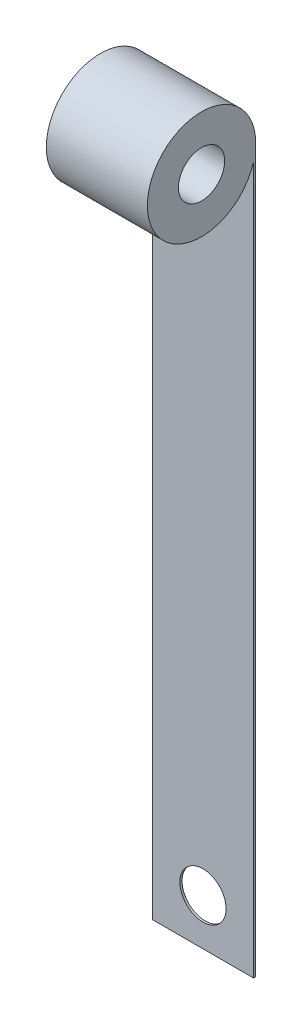
SolidWorks part; units mm, degrees
ref_plane "前视基准面" through (0, 0, 0) normal (0, 0, 1) x (1, 0, 0)
ref_plane "上视基准面" through (0, 0, 0) normal (0, 1, 0) x (1, 0, 0)
ref_plane "右视基准面" through (0, 0, 0) normal (1, 0, 0) x (0, 0, -1)
sketch "草图1" plane through (0, 0, 0) normal (1, 0, 0) x (0, 0, -1)
  circle A0 centre (0, 0) radius 3.75
  circle A1 centre (0, 0) radius 1.6
  dimension "D1" = 7.5
  dimension "D2" = 3.2
extrude "凸台-拉伸1" add sketch "草图1" along normal blind 7
sketch "草图2" plane through (0, 0, 0) normal (0, 1, 0) x (1, 0, 0)
  line L0 (7, -3.75) -> (7, 3.75) construction
  line L1 (0, 3.75) -> (7, 3.75)
  line L2 (0, 3.75) -> (0, 3.6)
  line L3 (0, 3.6) -> (7, 3.6)
  line L4 (7, 3.75) -> (7, 3.6)
  line L5 (0, 3.75) -> (7, 3.6) construction
  line L6 (0, 3.6) -> (7, 3.75) construction
  point P4 (3.5, 3.675)
  dimension "D1" = 0.15
extrude "凸台-拉伸2" add sketch "草图2" against normal blind 50
sketch "草图3" plane through (0, 0, -3.6) normal (0, 0, 1) x (1, 0, 0)
  line L0 (0, -50) -> (7, -50) construction
  circle A0 centre (3.5, -46.8) radius 1.6
  point P2 (0, 0)
  point P5 (3.5, -50)
  dimension "D1" = 3.2
  dimension "D2" = 3.2
extrude "切除-拉伸1" cut sketch "草图3" against normal through all
